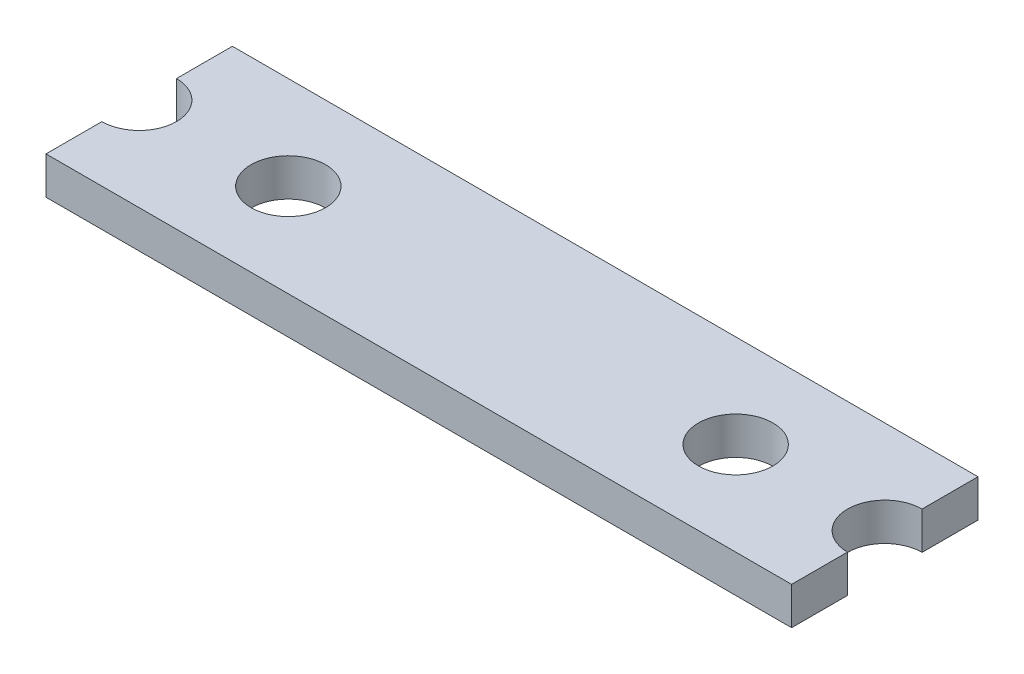
SolidWorks part; units mm, degrees
ref_plane "Front Plane" through (0, 0, 0) normal (0, 0, 1) x (1, 0, 0)
ref_plane "Top Plane" through (0, 0, 0) normal (0, 1, 0) x (1, 0, 0)
ref_plane "Right Plane" through (0, 0, 0) normal (1, 0, 0) x (0, 0, -1)
sketch "Sketch1" plane through (0, 0, 0) normal (0, 1, 0) x (1, 0, 0)
  line L1 (15.875, -3.9687) -> (-15.875, -3.9688)
  line L2 (15.875, -3.9687) -> (15.875, 3.9688)
  line L3 (15.875, 3.9688) -> (-15.875, 3.9687)
  line L4 (-15.875, -3.9688) -> (-15.875, 3.9687)
  line L5 (15.875, -3.9687) -> (-15.875, 3.9687) construction
  line L6 (15.875, 3.9688) -> (-15.875, -3.9688) construction
  point P0 (0, 0)
  dimension "D1" = 31.75
  dimension "D2" = 7.9375
extrude "Boss-Extrude1" add sketch "Sketch1" along normal blind 1.6
sketch "Sketch2" plane through (0, 1.6, 0) normal (0, 1, 0) x (1, 0, 0)
  line L0 (0, -3.9687) -> (0, 3.9688) construction
  line L1 (-15.875, -3.9688) -> (15.875, -3.9687) construction
  line L2 (15.875, 3.9688) -> (-15.875, 3.9687) construction
  line L3 (-15.875, 3.9687) -> (-15.875, -3.9688) construction
  line L4 (15.875, -3.9687) -> (15.875, 3.9688) construction
  line L5 (-15.875, 1.5875) -> (-15.875, -1.5875)
  line L6 (15.875, -1.5875) -> (15.875, 1.5875)
  circle A0 centre (-9.525, 0) radius 1.5875
  circle A1 centre (9.525, 0) radius 1.5875
  arc A2 (-15.875, -1.5875) -> (-15.875, 1.5875) centre (-15.875, 0) ccw
  arc A3 (15.875, 1.5875) -> (15.875, -1.5875) centre (15.875, 0) ccw
  dimension "D1" = 3.175
  dimension "D2" = 3.175
  dimension "D3" = 9.525
  dimension "D4" = 9.525
extrude "Cut-Extrude1" cut sketch "Sketch2" against normal through all
